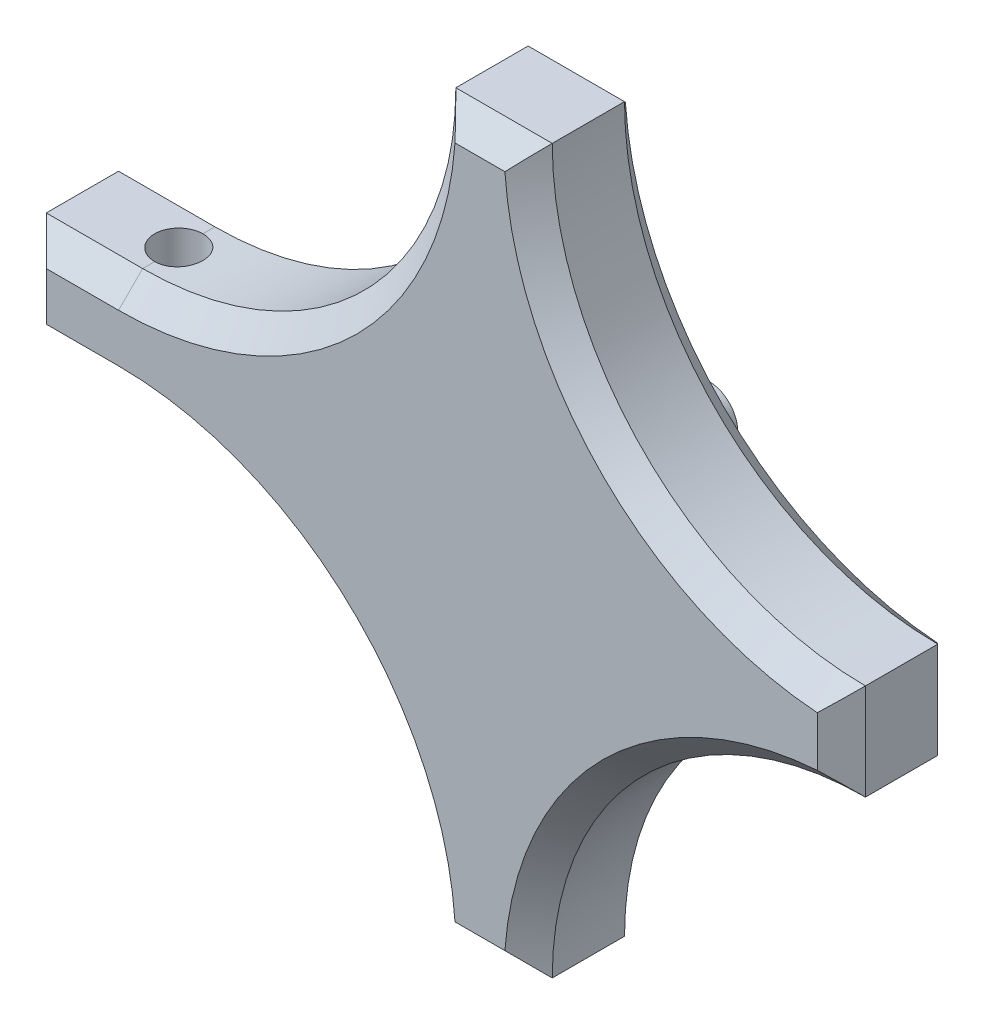
SolidWorks part; units mm, degrees
ref_plane "前视基准面" through (0, 0, 0) normal (0, 0, 1) x (1, 0, 0)
ref_plane "上视基准面" through (0, 0, 0) normal (0, 1, 0) x (1, 0, 0)
ref_plane "右视基准面" through (0, 0, 0) normal (1, 0, 0) x (0, 0, -1)
sketch "草图1" plane through (0, 0, 0) normal (0, 0, 1) x (1, 0, 0)
  line L1 (0, 0) -> (170, 0)
  line L2 (0, 0) -> (0, -150)
  line L3 (0, -150) -> (170, -150)
  line L4 (170, 0) -> (170, -150)
  dimension "D1" = 170
  dimension "D2" = 150
extrude "凸台-拉伸1" add sketch "草图1" along normal blind 25
sketch "草图3" plane through (0, 0, 0) normal (0, 0, -1) x (-1, 0, 0)
  line L0 (-105, 0) -> (-85, 0)
  line L1 (-170, 0) -> (0, 0) construction
  line L2 (-85, 0) -> (-20, 0)
  line L3 (0, -150) -> (-170, -150) construction
  line L4 (-20, -65) -> (0, -65)
  line L5 (0, 0) -> (0, -150) construction
  line L6 (0, -65) -> (0, -85)
  line L7 (0, -65) -> (0, -61.8466)
  line L8 (0, -61.8466) -> (0, -65)
  line L9 (-20, -85) -> (0, -85)
  line L10 (0, -85) -> (0, -88.1534)
  circle A0 centre (-170, 0) radius 65
  circle A1 centre (-170, -150) radius 65
  arc A2 (0, -61.8466) -> (-20, -65) centre (-20, 0) ccw
  arc A3 (-20, -85) -> (0, -88.1534) centre (-20, -150) ccw
  line M2 (0, -150) -> (0, 0)
  line M3 (0, 0) -> (-170, 0)
  line M4 (-170, 0) -> (-170, -150)
  line M5 (-170, -150) -> (0, -150)
  dimension "D1" = 130
  dimension "D2" = 130
  dimension "D4" = 130
  dimension "D5" = 130
  dimension "D3" = 65
  dimension "D6" = 150
extrude "切除-拉伸1" cut sketch "草图3" against normal blind 50 contours A0 M3 M4 | A0 M4 M3 | A2 M2 M3 | A2 L4 M3 M2 | A3 M5 M2 | L9 A3 M5 M2 | A1 M4 M5 | A1 M5 M4
chamfer "倒角2" distance 5 angle 45 10 edges at (170, -75, 0) (124.0381, -45.9619, 0) (95, 0, 0) (65.9619, -45.9619, 0) (10, -65, 0) (0, -75, 0) (10, -85, 0) (65.9619, -104.0381, 0) (95, -150, 0) (124.0381, -104.0381, 0)
ref_plane "基准面1" through (0, 0, 27.5) normal (0, 0, 1) x (1, 0, 0)
sketch "草图4" plane through (0, 0, 27.5) normal (0, 0, 1) x (1, 0, 0)
  line L2 (0, -65) -> (0, -150)
  line L3 (0, -150) -> (170, -150)
  line L4 (170, -65) -> (170, -150)
  line L6 (0, -65) -> (0, 0)
  line L7 (0, 0) -> (170, 0)
  line L8 (170, -65) -> (170, 0)
sketch "草图7" plane through (0, 0, 0) normal (0, 0, -1) x (-1, 0, 0)
  line L0 (0, 0) -> (0, -75) construction
  line L1 (0, -65) -> (0, -85) construction
  line L2 (0, -75) -> (-95, -75) construction
  line L4 (-107.5, -62.5) -> (-82.5, -62.5) construction
  line L5 (-107.5, -62.5) -> (-107.5, -87.5) construction
  line L6 (-107.5, -87.5) -> (-82.5, -87.5) construction
  line L7 (-82.5, -62.5) -> (-82.5, -87.5) construction
  line L8 (-107.5, -62.5) -> (-82.5, -87.5) construction
  line L9 (-107.5, -87.5) -> (-82.5, -62.5) construction
  circle A0 centre (-107.5, -62.5) radius 6
  circle A1 centre (-82.5, -62.5) radius 6
  circle A2 centre (-82.5, -87.5) radius 6
  circle A3 centre (-107.5, -87.5) radius 6
  dimension "D4" = 12
  dimension "D5" = 12
  dimension "D6" = 12
  dimension "D7" = 12
  dimension "D1" = 95
  dimension "D2" = 25
  dimension "D3" = 25
extrude "凸台-拉伸4" add sketch "草图7" along normal blind 10
chamfer "倒角4" distance 5 angle 45 10 edges at (95, -150, 25) (65.9619, -104.0381, 25) (10, -85, 25) (0, -75, 25) (10, -65, 25) (65.9619, -45.9619, 25) (95, 0, 25) (124.0381, -45.9619, 25) (170, -75, 25) (124.0381, -104.0381, 25)
sketch "草图8" plane through (0, 0, 0) normal (0, 1, 0) x (1, 0, 0)
  line L0 (0, -12.5) -> (20, -12.5) construction
  line L1 (0, -20) -> (0, -5) construction
  line L2 (20, -20) -> (20, -5) construction
  circle A0 centre (20, -12.5) radius 5
  dimension "D1" = 10
extrude "切除-拉伸2" cut sketch "草图8" against normal through all
